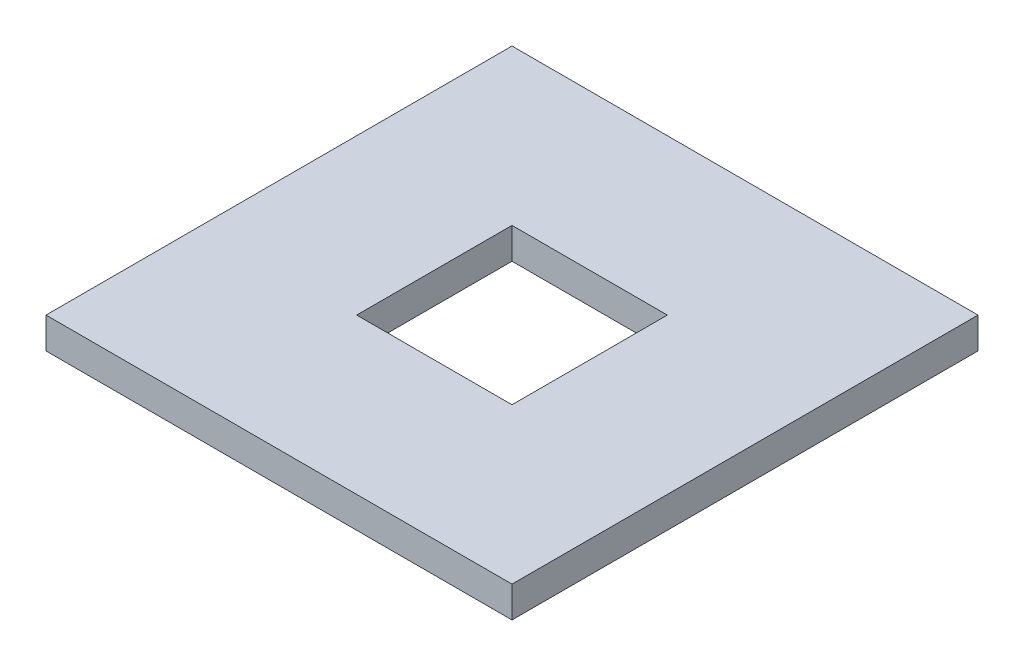
SolidWorks part; units mm, degrees
ref_plane "前视基准面" through (0, 0, 0) normal (0, 0, 1) x (1, 0, 0)
ref_plane "上视基准面" through (0, 0, 0) normal (0, 1, 0) x (1, 0, 0)
ref_plane "右视基准面" through (0, 0, 0) normal (1, 0, 0) x (0, 0, -1)
sketch "Sketch1" plane through (0, 0, 0) normal (0, 1, 0) x (1, 0, 0)
  line L1 (0, 0) -> (1500, 0)
  line L2 (0, 0) -> (0, 1500)
  line L3 (0, 1500) -> (1500, 1500)
  line L4 (1500, 0) -> (1500, 1500)
  line L5 (500, 1000) -> (1000, 1000)
  line L6 (500, 1000) -> (500, 500)
  line L7 (500, 500) -> (1000, 500)
  line L8 (1000, 1000) -> (1000, 500)
  dimension "D1" = 1500
  dimension "D2" = 1500
  dimension "D3" = 500
  dimension "D4" = 500
  dimension "D5" = 500
  dimension "D6" = 500
extrude "Boss-Extrude1" add sketch "Sketch1" along normal blind 100 contours L1 L4 L3 L2 L5 L8 L7 L6
